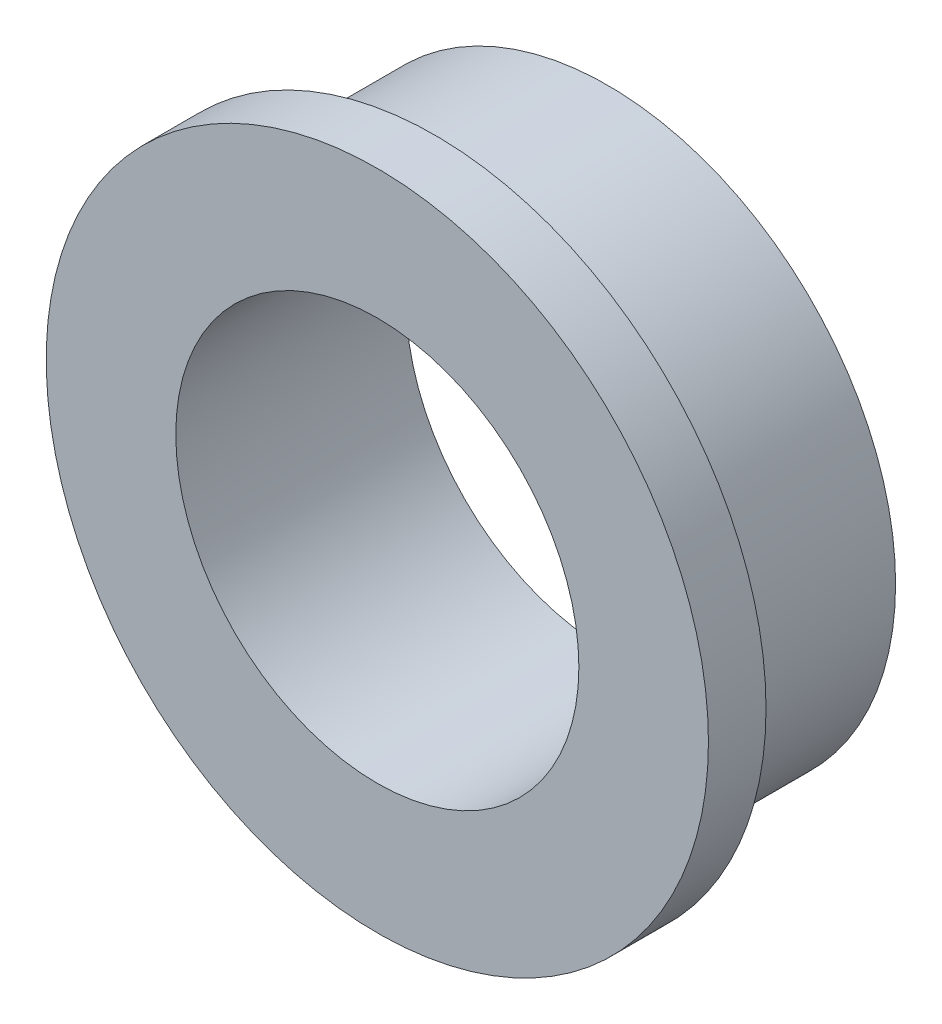
SolidWorks part; units mm, degrees
ref_plane "Alzado" through (0, 0, 0) normal (0, 0, 1) x (1, 0, 0)
ref_plane "Planta" through (0, 0, 0) normal (0, 1, 0) x (1, 0, 0)
ref_plane "Vista lateral" through (0, 0, 0) normal (1, 0, 0) x (0, 0, -1)
sketch "Croquis1" plane through (0, 0, 0) normal (0, 0, 1) x (1, 0, 0)
  circle A0 centre (0, 0) radius 5
  circle A1 centre (0, 0) radius 1.5
  circle A2 centre (0, 0) radius 3.5
  dimension "D1" = 10
  dimension "D2" = 3
  dimension "D3" = 7
extrude "Saliente-Extruir1" add sketch "Croquis1" along normal blind 4 contours A0 A2
sketch "Croquis2" plane through (0, 0, 4) normal (0, 0, 1) x (1, 0, 0)
  circle A0 centre (0, 0) radius 5.75
  circle A1 centre (0, 0) radius 5 construction
  circle A2 centre (0, 0) radius 5
  dimension "D1" = 11.5
extrude "Saliente-Extruir2" add sketch "Croquis2" against normal blind 1
